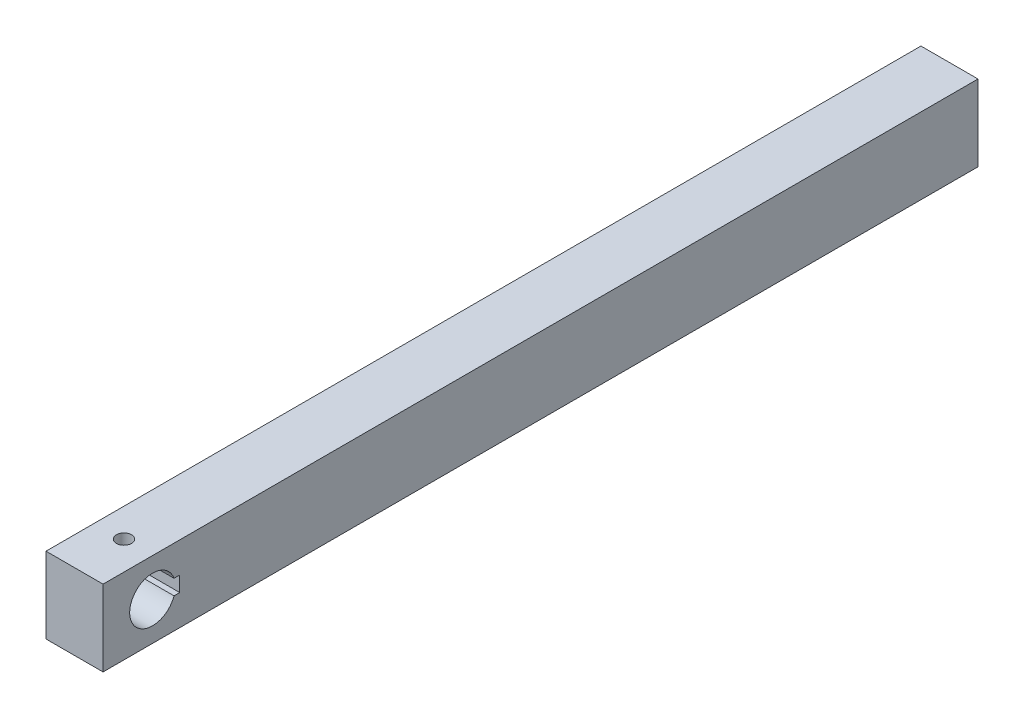
SolidWorks part; units mm, degrees
ref_plane "Front Plane" through (0, 0, 0) normal (0, 0, 1) x (1, 0, 0)
ref_plane "Top Plane" through (0, 0, 0) normal (0, 1, 0) x (1, 0, 0)
ref_plane "Right Plane" through (0, 0, 0) normal (1, 0, 0) x (0, 0, -1)
sketch "Sketch1" plane through (0, 0, 0) normal (0, 0, 1) x (1, 0, 0)
  line L1 (-7.5, 10) -> (7.5, 10)
  line L2 (-7.5, 10) -> (-7.5, -10)
  line L3 (-7.5, -10) -> (7.5, -10)
  line L4 (7.5, 10) -> (7.5, -10)
  line L5 (-7.5, 10) -> (7.5, -10) construction
  line L6 (-7.5, -10) -> (7.5, 10) construction
  point P0 (0, 0)
  dimension "D1" = 15
  dimension "D2" = 20
extrude "Boss-Extrude1" add sketch "Sketch1" along normal blind 230
sketch "Sketch2" plane through (0, 0, 0) normal (0, 0, -1) x (-1, 0, 0)
  line L1 (-32.5, 10) -> (32.5, 10)
  line L2 (-32.5, 10) -> (-32.5, 50)
  line L3 (-32.5, 50) -> (32.5, 50)
  line L4 (32.5, 10) -> (32.5, 50)
  line L6 (-7.5, 10) -> (7.5, 10) construction
  point P4 (0, 10)
  point P10 (0, 10)
  dimension "D1" = 65
  dimension "D2" = 40
extrude "Boss-Extrude6" add sketch "Sketch2" against normal blind 5 separate body
sketch "Sketch7" plane through (32.5, 0, 0) normal (1, 0, 0) x (0, 0, -1)
  line L0 (0, 50) -> (0, 10) construction
  line L1 (0, 37.5) -> (-75, 37.5)
  line L2 (0, 37.5) -> (0, 22.5)
  line L3 (0, 22.5) -> (-75, 22.5)
  line L4 (-75, 37.5) -> (-75, 22.5)
  point P4 (0, 30)
  point P7 (0, 30)
  dimension "D1" = 15
  dimension "D2" = 75
extrude "Boss-Extrude7" add sketch "Sketch7" along normal blind 5 separate body
sketch "Sketch8" plane through (-32.5, 0, 0) normal (-1, 0, 0) x (0, 0, 1)
  line L1 (0, 37.5) -> (75, 37.5)
  line L2 (0, 37.5) -> (0, 22.5)
  line L3 (0, 22.5) -> (75, 22.5)
  line L4 (75, 37.5) -> (75, 22.5)
extrude "Boss-Extrude8" add sketch "Sketch8" along normal blind 5 separate body
sketch "Sketch9" plane through (0, 0, 75) normal (0, 0, 1) x (1, 0, 0)
  line L1 (-32.5, 50) -> (32.5, 50)
  line L2 (-32.5, 50) -> (-32.5, 10)
  line L3 (-32.5, 10) -> (32.5, 10)
  line L4 (32.5, 50) -> (32.5, 10)
extrude "Boss-Extrude11" add sketch "Sketch9" against normal blind 5 separate body
sketch "Sketch10" plane through (-7.5, 0, 0) normal (-1, 0, 0) x (0, 0, 1)
  line L0 (230, 10) -> (230, -10) construction
  line L2 (209.8431, 2) -> (211.3431, 2)
  line L3 (209.8431, 2) -> (209.8431, -2)
  line L4 (209.8431, -2) -> (211.3431, -2)
  line L6 (209.8431, 2) -> (211, 0) construction
  line L7 (209.8431, -2) -> (211, 0) construction
  arc A0 (211.3431, -2) -> (211.3431, 2) centre (217, 0) ccw
  point P4 (230, 0)
  point P5 (211, 0)
  point P11 (209.8431, 0)
  dimension "D1" = 12
  dimension "D2" = 13
  dimension "D3" = 1.5
  dimension "D4" = 4
extrude "Cut-Extrude1" cut sketch "Sketch10" against normal through all
sketch "Sketch11" plane through (0, 0, 0) normal (1, 0, 0) x (0, 0, -1)
  point P0 (-217, 0)
sketch "Sketch12" plane through (0, 10, 0) normal (0, 1, 0) x (1, 0, 0)
  line L0 (-32.5, -5) -> (32.5, -5) construction
  point P0 (0, -36.5)
  point P3 (0, 0)
  dimension "D1" = 31.5
sketch "Sketch13" plane through (0, 10, 0) normal (0, 1, 0) x (1, 0, 0)
  circle A0 centre (0, -217) radius 1.9844
  dimension "D1" = 3.9688
extrude "Cut-Extrude2" cut sketch "Sketch13" against normal blind 10
delete or keep bodies "Body-Delete/Keep 1" type delete bodies bodies 106 107 108 109
